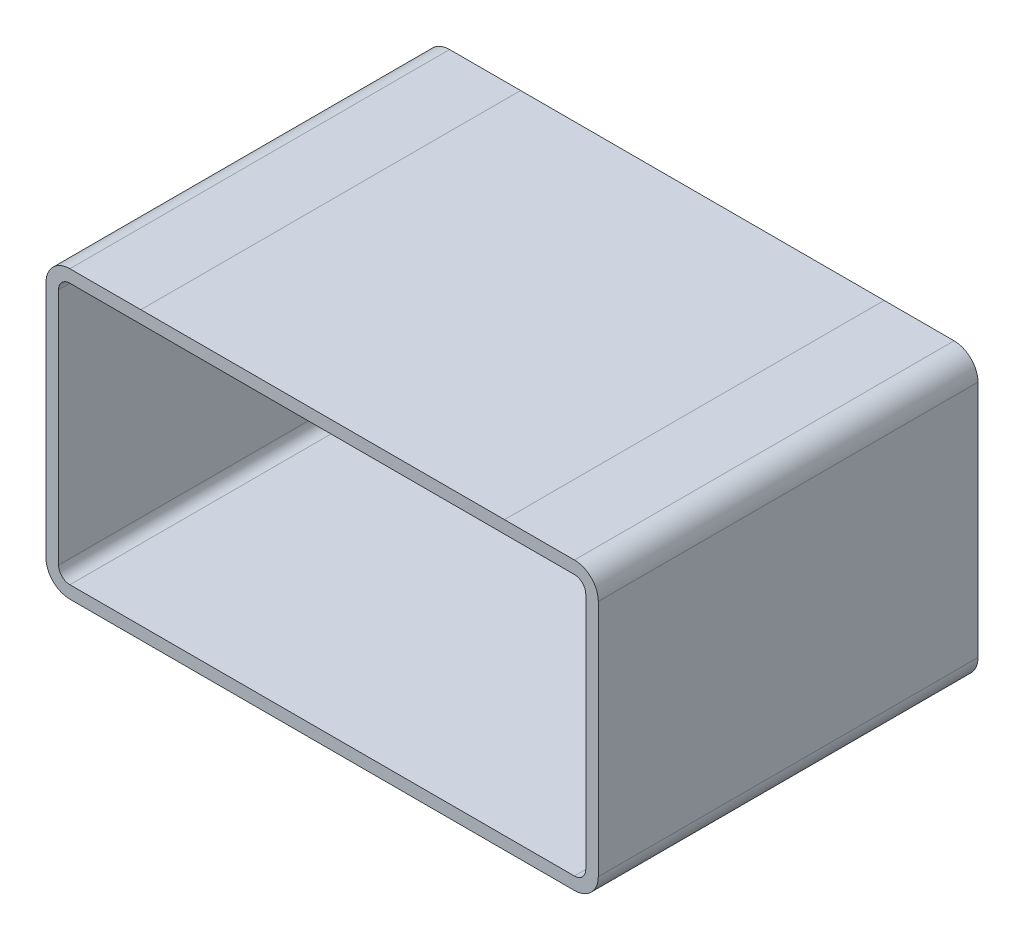
SolidWorks part; units mm, degrees
ref_plane "Front Plane" through (0, 0, 0) normal (0, 0, 1) x (1, 0, 0)
ref_plane "Top Plane" through (0, 0, 0) normal (0, 1, 0) x (1, 0, 0)
ref_plane "Right Plane" through (0, 0, 0) normal (1, 0, 0) x (0, 0, -1)
sketch "Sketch1" plane through (0, 0, 33.2132) normal (0, 0, -1) x (-1, 0, 0)
  line L0 (-63.6039, 45.4605) -> (-60.5528, 45.4605) construction
  line L1 (-18.649, 45.4604) -> (-15.5979, 45.4604) construction
  line L2 (-18.649, 45.4604) -> (-60.5528, 45.4605) construction
  line L3 (-11.0259, 50.0323) -> (-11.0259, 65.0183) construction
  line L4 (-15.5979, 69.5904) -> (-18.649, 69.5904) construction
  line L5 (-37.6009, 70.3404) -> (-37.6009, 69.5904) construction
  line L6 (-37.6009, 69.5904) -> (-18.649, 69.5904) construction
  line L7 (-41.6009, 70.3404) -> (-37.6009, 70.3404) construction
  line L8 (-41.6009, 69.5904) -> (-41.6009, 70.3404) construction
  line L9 (-68.1759, 65.0185) -> (-68.1759, 50.0325) construction
  line L10 (-60.5528, 69.5905) -> (-63.6039, 69.5905) construction
  line L11 (-60.5528, 69.5905) -> (-41.6009, 69.5904) construction
  line L12 (-81.7397, 76.7655) -> (-70.0331, 76.7655) construction
  line L13 (-85.7397, 40.4565) -> (-85.7397, 72.7655) construction
  line L14 (-85.7397, 40.4565) -> (-85.7397, 38.8565) construction
  line L15 (-85.7397, 32.8565) -> (-85.7397, 38.8565) construction
  line L16 (-81.7397, 28.8565) -> (2.7153, 28.8565) construction
  line L17 (6.7153, 32.8565) -> (6.7153, 38.8565) construction
  line L18 (6.7153, 40.4565) -> (6.7153, 38.8565) construction
  line L19 (6.7153, 72.7653) -> (6.7153, 40.4565) construction
  line L20 (-9.1686, 76.7653) -> (2.7153, 76.7653) construction
  line L21 (-70.0331, 76.7655) -> (-9.1686, 76.7653) construction
  line L22 (-63.6039, 45.4605) -> (-60.5528, 45.4605)
  line L23 (-18.649, 45.4604) -> (-15.5979, 45.4604)
  line L24 (-18.649, 45.4604) -> (-60.5528, 45.4605)
  line L25 (-11.0259, 50.0323) -> (-11.0259, 65.0183)
  line L26 (-15.5979, 69.5904) -> (-18.649, 69.5904)
  line L27 (-37.6009, 70.3404) -> (-37.6009, 69.5904)
  line L28 (-37.6009, 69.5904) -> (-18.649, 69.5904)
  line L29 (-41.6009, 70.3404) -> (-37.6009, 70.3404)
  line L30 (-41.6009, 69.5904) -> (-41.6009, 70.3404)
  line L31 (-68.1759, 65.0185) -> (-68.1759, 50.0325)
  line L32 (-60.5528, 69.5905) -> (-63.6039, 69.5905)
  line L33 (-60.5528, 69.5905) -> (-41.6009, 69.5904)
  line L34 (-81.7397, 76.7655) -> (-70.0331, 76.7655)
  line L35 (-85.7397, 40.4565) -> (-85.7397, 72.7655)
  line L36 (-85.7397, 40.4565) -> (-85.7397, 38.8565)
  line L37 (-85.7397, 32.8565) -> (-85.7397, 38.8565)
  line L38 (-81.7397, 28.8565) -> (2.7153, 28.8565)
  line L39 (6.7153, 32.8565) -> (6.7153, 38.8565)
  line L40 (6.7153, 40.4565) -> (6.7153, 38.8565)
  line L41 (6.7153, 72.7653) -> (6.7153, 40.4565)
  line L42 (-9.1686, 76.7653) -> (2.7153, 76.7653)
  line L43 (-70.0331, 76.7655) -> (-9.1686, 76.7653)
  circle A0 centre (-2.7646, 57.5253) radius 2.449 construction
  circle A1 centre (-76.4372, 57.5255) radius 2.449 construction
  arc A2 (-68.1759, 50.0325) -> (-63.6039, 45.4605) centre (-63.6039, 50.0325) ccw construction
  arc A3 (-15.5979, 45.4604) -> (-11.0259, 50.0323) centre (-15.5979, 50.0324) ccw construction
  arc A4 (-11.0259, 65.0183) -> (-15.5979, 69.5904) centre (-15.5979, 65.0184) ccw construction
  arc A5 (-63.6039, 69.5905) -> (-68.1759, 65.0185) centre (-63.6039, 65.0185) ccw construction
  arc A6 (-81.7397, 76.7655) -> (-85.7397, 72.7655) centre (-81.7397, 72.7655) ccw construction
  arc A7 (-85.7397, 32.8565) -> (-81.7397, 28.8565) centre (-81.7397, 32.8565) ccw construction
  arc A8 (2.7153, 28.8565) -> (6.7153, 32.8565) centre (2.7153, 32.8565) ccw construction
  arc A9 (6.7153, 72.7653) -> (2.7153, 76.7653) centre (2.7153, 72.7653) ccw construction
  circle A10 centre (-2.7646, 57.5253) radius 2.449
  circle A11 centre (-76.4372, 57.5255) radius 2.449
  arc A12 (-68.1759, 50.0325) -> (-63.6039, 45.4605) centre (-63.6039, 50.0325) ccw
  arc A13 (-15.5979, 45.4604) -> (-11.0259, 50.0323) centre (-15.5979, 50.0324) ccw
  arc A14 (-11.0259, 65.0183) -> (-15.5979, 69.5904) centre (-15.5979, 65.0184) ccw
  arc A15 (-63.6039, 69.5905) -> (-68.1759, 65.0185) centre (-63.6039, 65.0185) ccw
  arc A16 (-81.7397, 76.7655) -> (-85.7397, 72.7655) centre (-81.7397, 72.7655) ccw
  arc A17 (-85.7397, 32.8565) -> (-81.7397, 28.8565) centre (-81.7397, 32.8565) ccw
  arc A18 (2.7153, 28.8565) -> (6.7153, 32.8565) centre (2.7153, 32.8565) ccw
  arc A19 (6.7153, 72.7653) -> (2.7153, 76.7653) centre (2.7153, 72.7653) ccw
extrude "Boss-Extrude1" add sketch "Sketch1" along normal blind 2
sketch "Sketch2" plane through (0, 0, 33.2132) normal (0, 0, 1) x (1, 0, 0)
  line L0 (81.7397, 28.8565) -> (-2.7153, 28.8565) construction
  line L1 (85.7397, 72.7655) -> (85.7397, 32.8565) construction
  line L2 (70.0331, 76.7655) -> (81.7397, 76.7655) construction
  line L3 (-6.7153, 32.8565) -> (-6.7153, 72.7653) construction
  line L4 (9.1686, 76.7653) -> (70.0331, 76.7655) construction
  line L5 (-2.7153, 76.7653) -> (9.1686, 76.7653) construction
  line L6 (81.7397, 28.8565) -> (-2.7153, 28.8565)
  line L7 (85.7397, 72.7655) -> (85.7397, 32.8565)
  line L8 (70.0331, 76.7655) -> (81.7397, 76.7655)
  line L9 (-6.7153, 32.8565) -> (-6.7153, 72.7653)
  line L10 (9.1686, 76.7653) -> (70.0331, 76.7655)
  line L11 (-2.7153, 76.7653) -> (9.1686, 76.7653)
  line L12 (9.1686, 74.6653) -> (70.0331, 74.6655)
  line L13 (70.0331, 74.6655) -> (81.7397, 74.6655)
  line L14 (83.6397, 72.7655) -> (83.6397, 32.8565)
  line L15 (81.7397, 30.9565) -> (-2.7153, 30.9565)
  line L16 (-4.6153, 32.8565) -> (-4.6153, 72.7653)
  line L17 (-2.7153, 74.6653) -> (9.1686, 74.6653)
  arc A0 (81.7397, 28.8565) -> (85.7397, 32.8565) centre (81.7397, 32.8565) ccw construction
  arc A1 (-6.7153, 32.8565) -> (-2.7153, 28.8565) centre (-2.7153, 32.8565) ccw construction
  arc A2 (85.7397, 72.7655) -> (81.7397, 76.7655) centre (81.7397, 72.7655) ccw construction
  arc A3 (-2.7153, 76.7653) -> (-6.7153, 72.7653) centre (-2.7153, 72.7653) ccw construction
  arc A4 (81.7397, 28.8565) -> (85.7397, 32.8565) centre (81.7397, 32.8565) ccw
  arc A5 (-6.7153, 32.8565) -> (-2.7153, 28.8565) centre (-2.7153, 32.8565) ccw
  arc A6 (85.7397, 72.7655) -> (81.7397, 76.7655) centre (81.7397, 72.7655) ccw
  arc A7 (-2.7153, 76.7653) -> (-6.7153, 72.7653) centre (-2.7153, 72.7653) ccw
  arc A8 (83.6397, 72.7655) -> (81.7397, 74.6655) centre (81.7397, 72.7655) ccw
  arc A9 (81.7397, 30.9565) -> (83.6397, 32.8565) centre (81.7397, 32.8565) ccw
  arc A10 (-4.6153, 32.8565) -> (-2.7153, 30.9565) centre (-2.7153, 32.8565) ccw
  arc A11 (-2.7153, 74.6653) -> (-4.6153, 72.7653) centre (-2.7153, 72.7653) ccw
  dimension "D1" = 2.1
extrude "Boss-Extrude2" add sketch "Sketch2" along normal up to surface (61.56 mm away)
